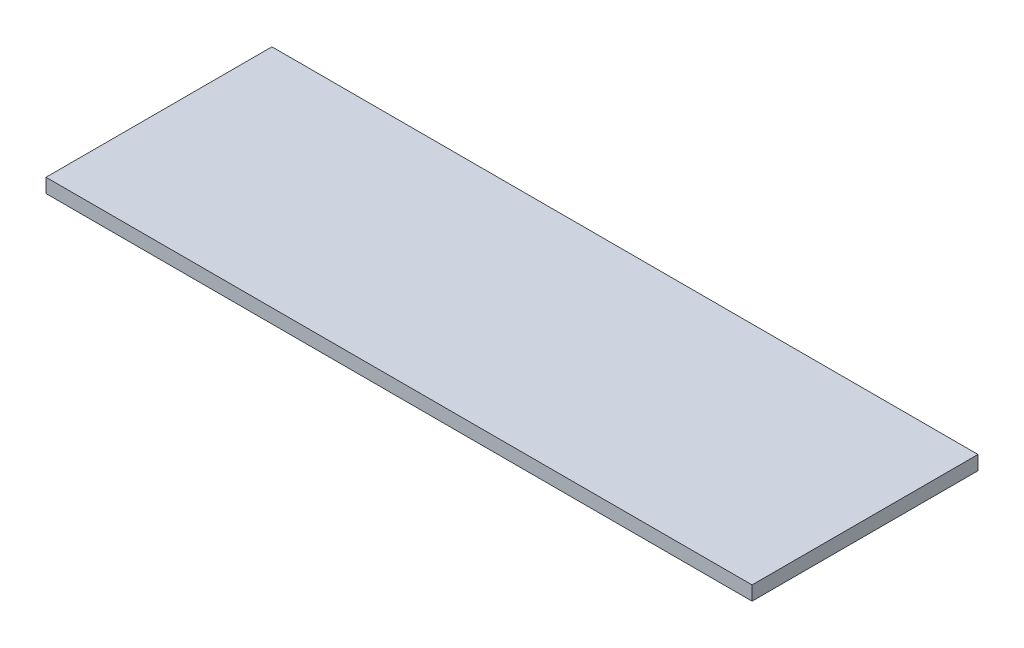
SolidWorks part; units mm, degrees
ref_plane "Front Plane" through (0, 0, 0) normal (0, 0, 1) x (1, 0, 0)
ref_plane "Top Plane" through (0, 0, 0) normal (0, 1, 0) x (1, 0, 0)
ref_plane "Right Plane" through (0, 0, 0) normal (1, 0, 0) x (0, 0, -1)
sketch "Sketch1" plane through (0, 0, 0) normal (0, 1, 0) x (1, 0, 0)
  line L1 (-317.5, -101.6) -> (317.5, -101.6)
  line L2 (-317.5, -101.6) -> (-317.5, 101.6)
  line L3 (-317.5, 101.6) -> (317.5, 101.6)
  line L4 (317.5, -101.6) -> (317.5, 101.6)
  line L5 (-317.5, -101.6) -> (317.5, 101.6) construction
  line L6 (-317.5, 101.6) -> (317.5, -101.6) construction
  point P0 (0, 0)
  dimension "D1" = 203.2
  dimension "D2" = 635
extrude "Boss-Extrude1" add sketch "Sketch1" along normal blind 12.7
